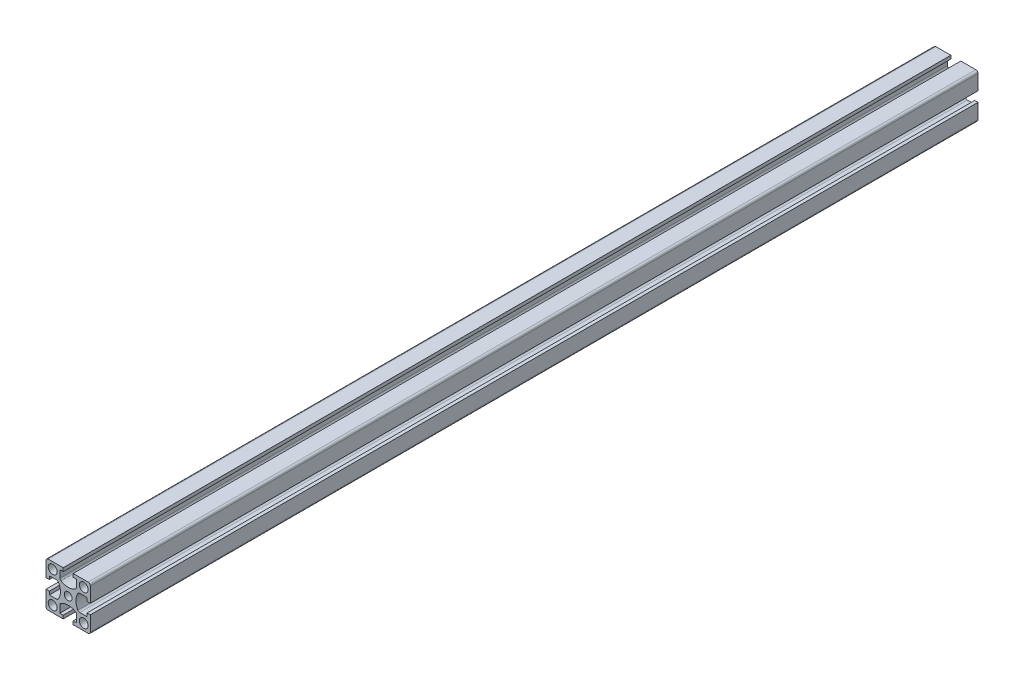
SolidWorks part; units mm, degrees
ref_plane "Front Plane" through (0, 0, 0) normal (0, 0, 1) x (1, 0, 0)
ref_plane "Top Plane" through (0, 0, 0) normal (0, 1, 0) x (1, 0, 0)
ref_plane "Right Plane" through (0, 0, 0) normal (1, 0, 0) x (0, 0, -1)
sketch "Sketch1" plane through (0, 0, 0) normal (0, 0, 1) x (1, 0, 0)
  line L64 (-10, 9) -> (-10, 2.25)
  line L65 (-10, 2.25) -> (-8.5, 2.25)
  line L66 (-8.5, 2.25) -> (-8.5, 3.75)
  line L67 (-8.5, 3.75) -> (-5.2369, 3.75)
  line L68 (-5.2369, -3.75) -> (-8.5, -3.75)
  line L69 (-8.5, -3.75) -> (-8.5, -2.25)
  line L70 (-8.5, -2.25) -> (-10, -2.25)
  line L71 (-10, -2.25) -> (-10, -9)
  line L72 (-9, -10) -> (-2.25, -10)
  line L73 (-2.25, -10) -> (-2.25, -8.5)
  line L74 (-2.25, -8.5) -> (-3.75, -8.5)
  line L75 (-3.75, -8.5) -> (-3.75, -5.2369)
  line L76 (3.75, -5.2369) -> (3.75, -8.5)
  line L77 (3.75, -8.5) -> (2.25, -8.5)
  line L78 (2.25, -8.5) -> (2.25, -10)
  line L79 (2.25, -10) -> (9, -10)
  line L80 (10, -9) -> (10, -2.25)
  line L81 (10, -2.25) -> (8.5, -2.25)
  line L82 (8.5, -2.25) -> (8.5, -3.75)
  line L83 (8.5, -3.75) -> (5.2369, -3.75)
  line L84 (5.2369, 3.75) -> (8.5, 3.75)
  line L85 (8.5, 3.75) -> (8.5, 2.25)
  line L86 (8.5, 2.25) -> (10, 2.25)
  line L87 (10, 2.25) -> (10, 9)
  line L88 (9, 10) -> (2.25, 10)
  line L89 (2.25, 10) -> (2.25, 8.5)
  line L90 (2.25, 8.5) -> (3.75, 8.5)
  line L91 (3.75, 8.5) -> (3.75, 5.2369)
  line L92 (-3.75, 5.2369) -> (-3.75, 8.5)
  line L93 (-3.75, 8.5) -> (-2.25, 8.5)
  line L94 (-2.25, 8.5) -> (-2.25, 10)
  line L95 (-2.25, 10) -> (-9, 10)
  circle A5 centre (-7, -7) radius 2
  circle A6 centre (7, -7) radius 2
  circle A7 centre (7, 7) radius 2
  circle A8 centre (0, 0) radius 1.75
  circle A9 centre (-7, 7) radius 2
  arc A32 (-9, 10) -> (-10, 9) centre (-9, 9) ccw
  arc A33 (-4.3708, 3.25) -> (-5.2369, 3.75) centre (-5.2369, 2.75) ccw
  arc A34 (-4.3708, -3.25) -> (-4.3708, 3.25) centre (-10, 0) ccw
  arc A35 (-5.2369, -3.75) -> (-4.3708, -3.25) centre (-5.2369, -2.75) ccw
  arc A36 (-10, -9) -> (-9, -10) centre (-9, -9) ccw
  arc A37 (-3.25, -4.3708) -> (-3.75, -5.2369) centre (-2.75, -5.2369) ccw
  arc A38 (3.25, -4.3708) -> (-3.25, -4.3708) centre (0, -10) ccw
  arc A39 (3.75, -5.2369) -> (3.25, -4.3708) centre (2.75, -5.2369) ccw
  arc A40 (9, -10) -> (10, -9) centre (9, -9) ccw
  arc A41 (4.3708, -3.25) -> (5.2369, -3.75) centre (5.2369, -2.75) ccw
  arc A42 (4.3708, 3.25) -> (4.3708, -3.25) centre (10, 0) ccw
  arc A43 (5.2369, 3.75) -> (4.3708, 3.25) centre (5.2369, 2.75) ccw
  arc A44 (10, 9) -> (9, 10) centre (9, 9) ccw
  arc A45 (3.25, 4.3708) -> (3.75, 5.2369) centre (2.75, 5.2369) ccw
  arc A46 (-3.25, 4.3708) -> (3.25, 4.3708) centre (0, 10) ccw
  arc A47 (-3.75, 5.2369) -> (-3.25, 4.3708) centre (-2.75, 5.2369) ccw
extrude "Boss-Extrude1" add sketch "Sketch1" along normal blind 400
